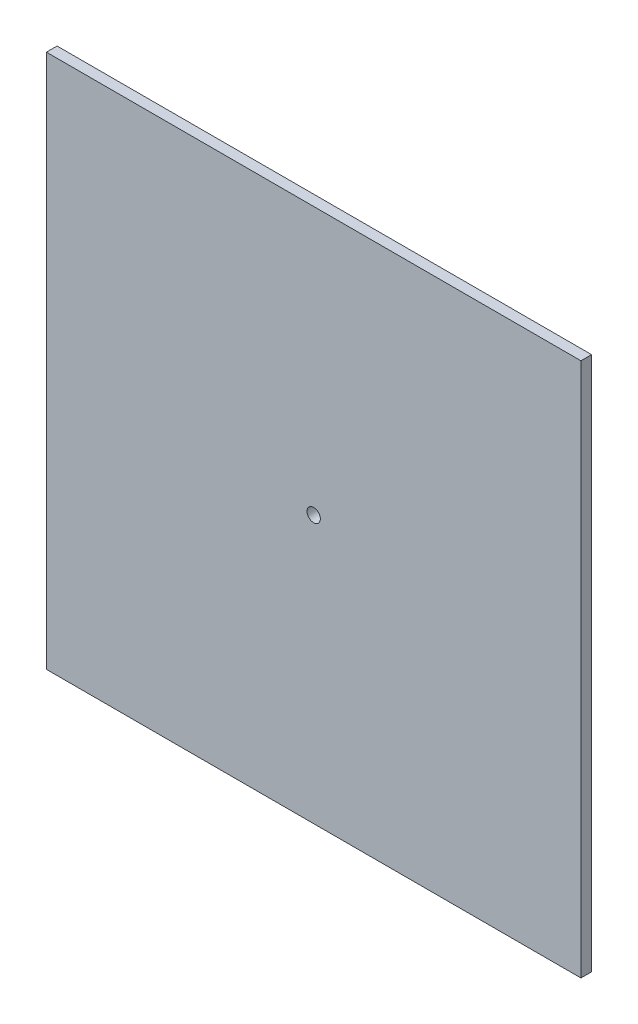
SolidWorks part; units mm, degrees
ref_plane "Front Plane" through (0, 0, 0) normal (0, 0, 1) x (1, 0, 0)
ref_plane "Top Plane" through (0, 0, 0) normal (0, 1, 0) x (1, 0, 0)
ref_plane "Right Plane" through (0, 0, 0) normal (1, 0, 0) x (0, 0, -1)
sketch "Sketch1" plane through (0, 0, 0) normal (0, 0, 1) x (1, 0, 0)
  line L1 (-100.4, 100.4) -> (100.4, 100.4)
  line L2 (-100.4, 100.4) -> (-100.4, -100.4)
  line L3 (-100.4, -100.4) -> (100.4, -100.4)
  line L4 (100.4, 100.4) -> (100.4, -100.4)
  line L5 (-100.4, 100.4) -> (100.4, -100.4) construction
  line L6 (-100.4, -100.4) -> (100.4, 100.4) construction
  circle A0 centre (0, 0) radius 2.5
  point P0 (0, 0)
  dimension "D3" = 5
  dimension "D1" = 200.8
  dimension "D2" = 200.8
extrude "Boss-Extrude2" add sketch "Sketch1" along normal blind 4
